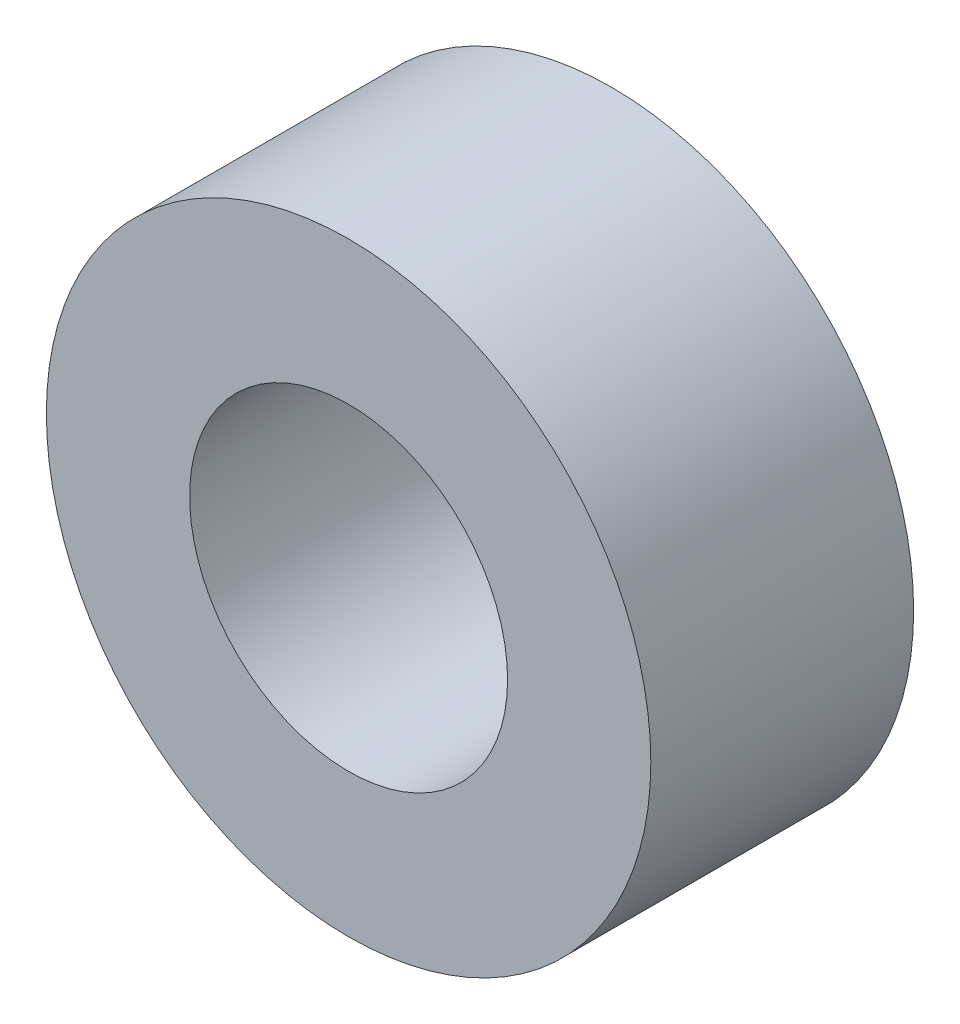
SolidWorks part; units mm, degrees
material "Custom Plastic"
ref_plane "X-Y Datum" through (0, 0, 0) normal (0, 0, 1) x (1, 0, 0)
ref_plane "X-Z Datum" through (0, 0, 0) normal (0, 1, 0) x (1, 0, 0)
ref_plane "Y-Z Datum" through (0, 0, 0) normal (1, 0, 0) x (0, 0, -1)
sketch "Sketch1" plane through (0, 0, 0) normal (0, 0, 1) x (1, 0, 0)
  circle A0 centre (0, 0) radius 5.75
  dimension "D1" = 11.5
extrude "Boss-Extrude1" add sketch "Sketch1" along normal blind 5
sketch "Sketch2" plane through (0, 0, 5) normal (0, 0, 1) x (1, 0, 0)
  circle A0 centre (0, 0) radius 3.025
  dimension "D1" = 6.05
extrude "Cut-Extrude1" cut sketch "Sketch2" against normal blind 4.8
